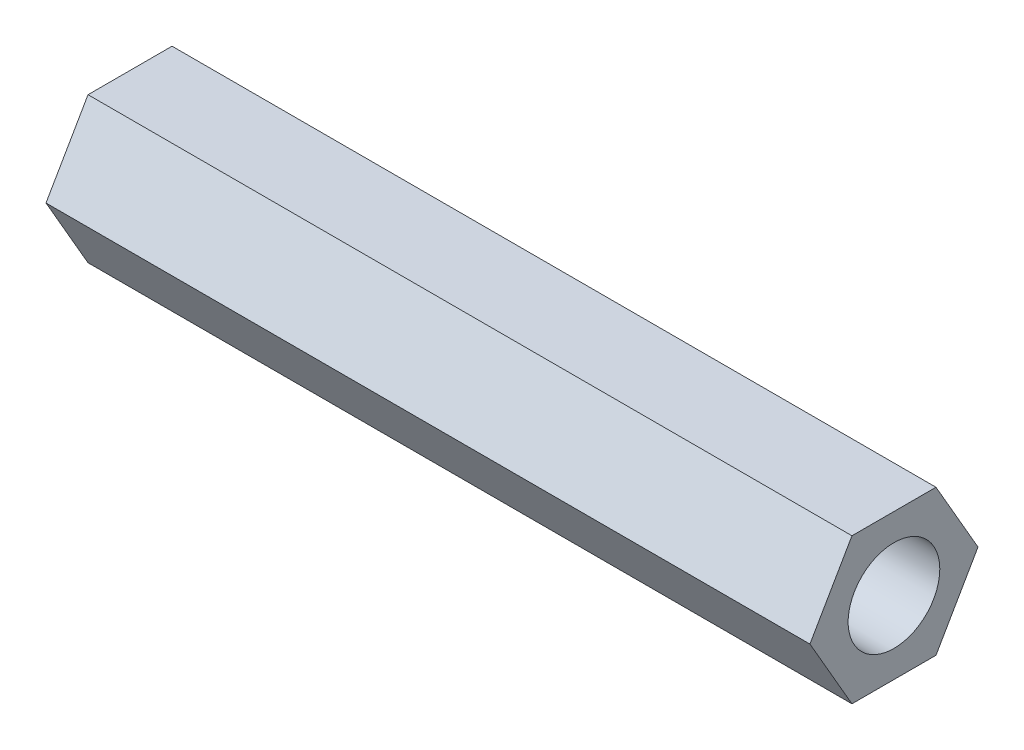
SolidWorks part; units mm, degrees
ref_plane "前视基准面" through (0, 0, 0) normal (0, 0, 1) x (1, 0, 0)
ref_plane "上视基准面" through (0, 0, 0) normal (0, 1, 0) x (1, 0, 0)
ref_plane "右视基准面" through (0, 0, 0) normal (1, 0, 0) x (0, 0, -1)
sketch "草图1" plane through (0, 0, 0) normal (1, 0, 0) x (0, 0, -1)
  line L1 (2.75, 0) -> (1.375, 2.3816)
  line L2 (1.375, 2.3816) -> (-1.375, 2.3816)
  line L3 (-1.375, 2.3816) -> (-2.75, 0)
  line L4 (-2.75, 0) -> (-1.375, -2.3816)
  line L5 (-1.375, -2.3816) -> (1.375, -2.3816)
  line L6 (1.375, -2.3816) -> (2.75, 0)
  circle A0 centre (0, 0) radius 2.75 construction
  circle A1 centre (0, 0) radius 1.5
extrude "凸台-拉伸1" add sketch "草图1" along normal blind 25
